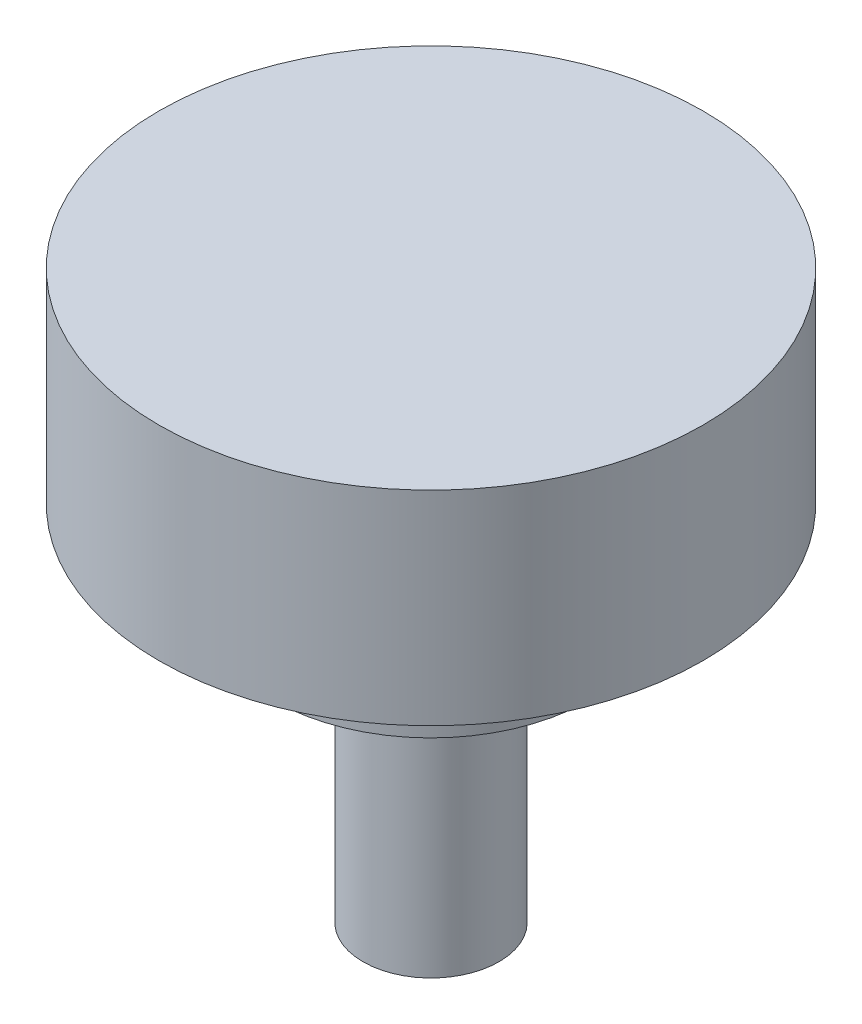
SolidWorks part; units mm, degrees
ref_plane "Plan de face" through (0, 0, 0) normal (0, 0, 1) x (1, 0, 0)
ref_plane "Plan de dessus" through (0, 0, 0) normal (0, 1, 0) x (1, 0, 0)
ref_plane "Plan de droite" through (0, 0, 0) normal (1, 0, 0) x (0, 0, -1)
sketch "Esquisse1" plane through (0, 0, 0) normal (0, 1, 0) x (1, 0, 0)
  circle A0 centre (0, 0) radius 3
  dimension "D1" = 6
extrude "Boss.-Extru.1" add sketch "Esquisse1" along normal blind 12
sketch "Esquisse2" plane through (0, 12, 0) normal (0, 1, 0) x (1, 0, 0)
  circle A0 centre (0, 0) radius 7
  dimension "D1" = 14
extrude "Boss.-Extru.2" add sketch "Esquisse2" along normal blind 4
sketch "Esquisse3" plane through (0, 16, 0) normal (0, 1, 0) x (1, 0, 0)
  circle A0 centre (0, 0) radius 12
  dimension "D1" = 24
extrude "Boss.-Extru.3" add sketch "Esquisse3" along normal blind 9
